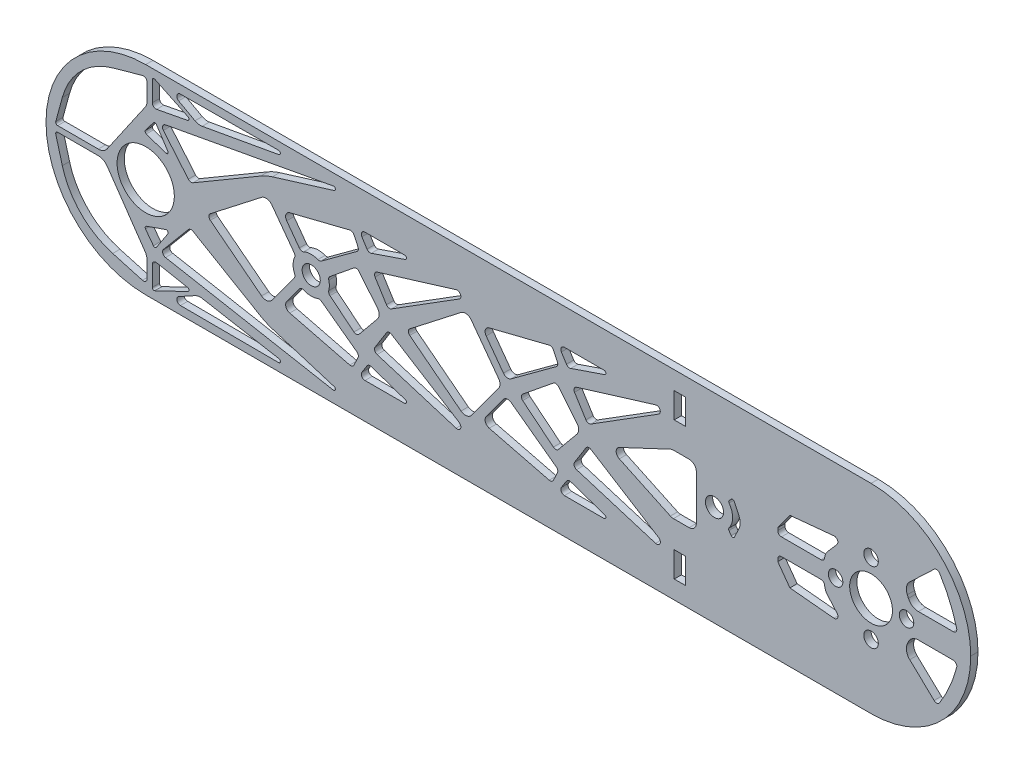
SolidWorks part; units mm, degrees
ref_plane "Front Plane" through (0, 0, 0) normal (0, 0, 1) x (1, 0, 0)
ref_plane "Top Plane" through (0, 0, 0) normal (0, 1, 0) x (1, 0, 0)
ref_plane "Right Plane" through (0, 0, 0) normal (1, 0, 0) x (0, 0, -1)
sketch "Sketch1" plane through (0, 0, 0) normal (0, 0, 1) x (1, 0, 0)
  line L1 (27.49, 0) -> (227.51, 0)
  line L2 (0, 27.49) -> (0, 27.51)
  line L3 (27.49, 55) -> (227.51, 55)
  line L4 (255, 27.49) -> (255, 27.51)
  arc A0 (227.51, 0) -> (255, 27.49) centre (227.51, 27.49) ccw
  arc A1 (227.51, 55) -> (255, 27.51) centre (227.51, 27.51) cw
  arc A2 (27.49, 0) -> (0, 27.49) centre (27.49, 27.49) cw
  arc A3 (27.49, 55) -> (0, 27.51) centre (27.49, 27.51) ccw
  point P9 (255, 55)
  point P12 (0, 0)
  point P15 (0, 55)
  dimension "D3" = 27.49
  dimension "D1" = 255
  dimension "D2" = 55
extrude "Boss-Extrude1" add sketch "Sketch1" along normal blind 2
sketch "Sketch2" plane through (0, 0, 2) normal (0, 0, 1) x (1, 0, 0)
  circle A0 centre (227.51, 27.51) radius 5.9
  circle A1 centre (27.49, 27.51) radius 7.9
  arc A2 (27.49, 55) -> (0, 27.51) centre (27.49, 27.51) ccw construction
  circle A3 centre (227.51, 27.51) radius 9.78
  circle A4 centre (217.73, 27.51) radius 2
  circle A5 centre (227.51, 37.29) radius 2
  circle A6 centre (237.29, 27.51) radius 2
  circle A7 centre (227.51, 17.73) radius 2
  point P17 (227.51, 27.51)
  dimension "D1" = 11.8
  dimension "D2" = 15.8
  dimension "D3" = 19.56
  dimension "D4" = 4
  dimension "D5" = 4
extrude "Cut-Extrude1" cut sketch "Sketch2" against normal through all contours A0 | A3 A5 | A3 A5 | A3 A4 | A3 A6 | A3 A6 | A3 A4 | A1 | A3 A7 | A3 A7
sketch "Sketch3" plane through (0, 0, 2) normal (0, 0, 1) x (1, 0, 0)
  line L5 (26.856, 20.2813) -> (28.4607, 20.2813)
  line L6 (26.856, 20.2813) -> (26.856, 19.5714)
  line L7 (26.856, 19.5714) -> (28.4607, 19.5714)
  line L8 (28.4607, 20.2813) -> (28.4607, 19.5714)
sketch "Sketch5" plane through (0, 0, 2) normal (0, 0, 1) x (1, 0, 0)
  line L0 (53.49, 5) -> (99.2465, 45)
  line L1 (53.49, 45) -> (99.2465, 45)
  line L2 (53.49, 45) -> (53.49, 5)
  line L3 (53.49, 5) -> (99.2465, 5)
  line L4 (99.2465, 45) -> (99.2465, 5)
  line L5 (53.49, 45) -> (99.2465, 5)
  line L6 (54.1482, 4.2471) -> (99.9046, 44.2471)
  line L7 (52.8318, 5.7529) -> (98.5883, 45.7529)
  line L8 (52.8318, 44.2471) -> (98.5883, 4.2471)
  line L9 (54.1482, 45.7529) -> (99.9046, 5.7529)
  line L10 (103.49, 5) -> (149.2465, 45)
  line L11 (103.49, 45) -> (149.2465, 45)
  line L12 (103.49, 45) -> (103.49, 5)
  line L13 (103.49, 5) -> (149.2465, 5)
  line L14 (149.2465, 45) -> (149.2465, 5)
  line L15 (103.49, 45) -> (149.2465, 5)
  line L16 (104.1482, 4.2471) -> (149.9046, 44.2471)
  line L17 (102.8318, 5.7529) -> (148.5883, 45.7529)
  line L18 (102.8318, 44.2471) -> (148.5883, 4.2471)
  line L19 (104.1482, 45.7529) -> (149.9046, 5.7529)
  line L20 (153.49, 5) -> (199.2465, 45)
  line L21 (153.49, 45) -> (199.2465, 45)
  line L22 (153.49, 45) -> (153.49, 5)
  line L23 (153.49, 5) -> (199.2465, 5)
  line L24 (199.2465, 45) -> (199.2465, 5)
  line L25 (153.49, 45) -> (199.2465, 5)
  line L26 (154.1482, 4.2471) -> (199.9046, 44.2471)
  line L27 (152.8318, 5.7529) -> (198.5883, 45.7529)
  line L28 (152.8318, 44.2471) -> (198.5883, 4.2471)
  line L29 (154.1482, 45.7529) -> (199.9046, 5.7529)
  line L30 (203.49, 5) -> (249.2465, 45)
  line L31 (203.49, 45) -> (249.2465, 45)
  line L32 (203.49, 45) -> (203.49, 5)
  line L33 (203.49, 5) -> (249.2465, 5)
  line L34 (249.2465, 45) -> (249.2465, 5)
  line L35 (203.49, 45) -> (249.2465, 5)
  line L36 (204.1482, 4.2471) -> (249.9046, 44.2471)
  line L37 (202.8318, 5.7529) -> (248.5883, 45.7529)
  line L38 (202.8318, 44.2471) -> (248.5883, 4.2471)
  line L39 (204.1482, 45.7529) -> (249.9046, 5.7529)
  line L40 (27.49, 0) -> (227.51, 0) construction
  line L41 (53.49, 25) -> (76.3682, 45)
  line L42 (76.3682, 45) -> (99.2465, 25)
  line L43 (99.2465, 25) -> (76.3682, 5)
  line L44 (76.3682, 5) -> (53.49, 25)
  line L45 (51.9706, 25) -> (76.3682, 46.3282)
  line L46 (76.3682, 46.3282) -> (100.7658, 25)
  line L47 (100.7658, 25) -> (76.3682, 3.6718)
  line L48 (76.3682, 3.6718) -> (51.9706, 25)
  line L49 (55.0094, 25) -> (76.3682, 43.6718)
  line L50 (76.3682, 43.6718) -> (97.7271, 25)
  line L51 (97.7271, 25) -> (76.3682, 6.3282)
  line L52 (76.3682, 6.3282) -> (55.0094, 25)
  line L53 (105.0094, 25) -> (126.3682, 43.6718)
  line L54 (101.9706, 25) -> (126.3682, 46.3282)
  line L55 (126.3682, 43.6718) -> (147.7271, 25)
  line L56 (126.3682, 46.3282) -> (150.7658, 25)
  line L57 (150.7658, 25) -> (126.3682, 3.6718)
  line L58 (147.7271, 25) -> (126.3682, 6.3282)
  line L59 (126.3682, 6.3282) -> (105.0094, 25)
  line L60 (126.3682, 3.6718) -> (101.9706, 25)
  line L61 (155.0094, 25) -> (176.3682, 43.6718)
  line L62 (151.9706, 25) -> (176.3682, 46.3282)
  line L63 (176.3682, 43.6718) -> (197.7271, 25)
  line L64 (176.3682, 46.3282) -> (200.7658, 25)
  line L65 (200.7658, 25) -> (176.3682, 3.6718)
  line L66 (197.7271, 25) -> (176.3682, 6.3282)
  line L67 (176.3682, 6.3282) -> (155.0094, 25)
  line L68 (176.3682, 3.6718) -> (151.9706, 25)
  line L69 (205.0094, 25) -> (226.3682, 43.6718)
  line L70 (201.9706, 25) -> (226.3682, 46.3282)
  line L71 (226.3682, 43.6718) -> (247.7271, 25)
  line L72 (226.3682, 46.3282) -> (250.7658, 25)
  line L73 (250.7658, 25) -> (226.3682, 3.6718)
  line L74 (247.7271, 25) -> (226.3682, 6.3282)
  line L75 (226.3682, 6.3282) -> (205.0094, 25)
  line L76 (226.3682, 3.6718) -> (201.9706, 25)
  dimension "D7" = 40
  dimension "D8" = 5
  dimension "D1" = 1
  dimension "D2" = 1
  dimension "D3" = 1
  dimension "D4" = 1
  dimension "D9" = 1
  dimension "D10" = 1
  dimension "D5" = 4
  dimension "D11" = 4
extrude "Cut-Extrude7" [suppressed] cut sketch "Sketch5" against normal blind 10 contours L75 L37 L38 L69 | L32 L70 L38 | L39 L70 L31 | L71 L69 L39 L37 | L31 L72 L37 | L36 L72 L34 | L74 L71 L36 L39 | L34 L73 L39 | L38 L73 L33 | L75 L74 L38 L36 | L33 L76 L36 | L37 L76 L32 | L24 L65 L29 | L28 L65 L23 | L67 L66 L28 L26 | L66 L63 L26 L29 | L26 L64 L24 | L21 L64 L27 | L63 L61 L29 L27 | L67 L27 L28 L61 | L27 L68 L22 | L23 L68 L26 | L22 L62 L28 | L29 L62 L21 | L18 L57 L13 | L14 L57 L19 | L58 L55 L16 L19 | L16 L56 L14 | L59 L58 L18 L16 | L13 L60 L16 | L17 L60 L12 | L59 L17 L18 L53 | L55 L53 L19 L17 | L11 L56 L17 | L19 L54 L11 | L12 L54 L18 | L4 L47 L9 | L8 L47 L3 | L52 L51 L8 L6 | L51 L50 L6 L9 | L6 L46 L4 | L1 L46 L7 | L50 L49 L9 L7 | L52 L7 L8 L49 | L2 L45 L8 | L7 L48 L2 | L3 L48 L6 | L9 L45 L1
sketch "Sketch7" plane through (0, 0, 2) normal (0, 0, 1) x (1, 0, 0)
  line L0 (0, 27.49) -> (255, 27.51) construction
  line L1 (59.4407, 39.2596) -> (45.3072, 28.2834)
  line L2 (46.3778, 27.4936) -> (70.6726, 27.4955)
  line L3 (69.7968, 26.3076) -> (62.2781, 16.1218)
  line L4 (69.7966, 28.6834) -> (62.2764, 38.868)
  line L5 (59.4426, 15.7298) -> (45.3073, 26.7037)
  line L6 (66.3676, 37.131) -> (71.1401, 30.6311)
  line L7 (73.2369, 30.3097) -> (85.7182, 39.4738)
  line L8 (86.0297, 40.7087) -> (84.9059, 43.0763)
  line L9 (83.7595, 43.6175) -> (67.2123, 39.4738)
  line L10 (87.1039, 43.6667) -> (88.5202, 41.4401)
  line L11 (89.6871, 41.0304) -> (99.0589, 44.2302)
  line L12 (98.8973, 45.2034) -> (87.9477, 45.2034)
  line L13 (90.7426, 35.8539) -> (93.8832, 30.8489)
  line L14 (95.2614, 30.5332) -> (113.9262, 42.2328)
  line L15 (113.1016, 44.0361) -> (91.2961, 37.3414)
  line L16 (158.0853, 28.8598) -> (183.7384, 40.9274)
  line L17 (185.729, 40.2195) -> (191.0035, 29.2363)
  line L18 (191.8349, 27.505) -> (155.1994, 27.5022)
  line L19 (185.731, 14.7897) -> (191.0038, 25.7737)
  line L20 (158.0855, 26.145) -> (183.7405, 14.0814)
  line L21 (76.448, 28.2722) -> (84.909, 35.1452)
  line L22 (86.3126, 35.0033) -> (91.43, 28.7656)
  line L23 (92.4706, 27.4973) -> (75.4923, 27.4959)
  line L24 (86.3138, 19.9903) -> (91.4302, 26.2288)
  line L25 (76.4481, 26.7198) -> (84.9102, 19.8481)
  line L26 (113.1042, 10.9617) -> (91.2977, 17.6529)
  line L27 (95.2619, 24.4618) -> (113.9285, 12.7651)
  line L28 (90.7439, 19.1403) -> (93.8838, 24.1458)
  line L29 (98.9001, 9.7921) -> (87.9505, 9.7904)
  line L30 (89.6892, 13.9636) -> (99.0615, 10.7653)
  line L31 (87.1065, 11.3269) -> (88.5224, 13.5538)
  line L32 (83.7621, 11.3756) -> (67.2142, 15.5167)
  line L33 (86.0318, 14.2848) -> (84.9083, 11.917)
  line L34 (73.2374, 24.6818) -> (85.72, 15.5196)
  line L35 (66.3691, 17.8594) -> (71.1406, 24.3601)
  line L36 (32.3699, 41.7077) -> (39.2566, 33.5015)
  line L37 (40.5286, 33.2818) -> (59.2382, 44.257)
  line L38 (62.4141, 45.6547) -> (79.4526, 50.9005)
  line L39 (79.2147, 51.8701) -> (32.9544, 43.334)
  line L40 (29.6243, 42.1853) -> (27.4391, 39.2765)
  line L41 (27.6724, 38.5047) -> (33.0193, 36.6169)
  line L42 (33.6032, 37.3636) -> (30.4415, 42.1602)
  line L43 (33.6048, 17.6217) -> (30.4438, 12.8246)
  line L44 (27.6741, 16.4797) -> (33.0207, 18.3683)
  line L45 (29.6266, 12.7993) -> (27.441, 15.7078)
  line L46 (79.2185, 3.1224) -> (32.9569, 11.6512)
  line L47 (62.4169, 9.3351) -> (79.4562, 4.092)
  line L48 (40.5295, 21.7046) -> (59.2408, 10.7323)
  line L49 (32.3721, 13.2774) -> (39.2575, 21.4847)
  line L50 (41.0795, 48.3745) -> (36.5711, 50.8626)
  line L51 (37.0652, 52.7381) -> (64.1368, 52.8435)
  line L52 (64.2272, 51.8514) -> (43.0596, 48.0483)
  line L53 (3.2327, 28.2834) -> (14.4162, 28.2834)
  line L54 (16.8868, 29.5817) -> (27.3295, 44.7433)
  line L55 (27.8588, 46.445) -> (27.8588, 50.9822)
  line L56 (2.6923, 28.9903) -> (4.4983, 35.6339)
  line L57 (18.3898, 49.6422) -> (26.5884, 51.945)
  line L58 (29.3043, 52.2893) -> (29.3043, 46.7923)
  line L59 (30.4915, 45.81) -> (39.0051, 47.4324)
  line L60 (39.1277, 48.3745) -> (30.0204, 52.7401)
  line L61 (39.1309, 6.6117) -> (30.0244, 2.2446)
  line L62 (30.4944, 9.1748) -> (39.0083, 7.5537)
  line L63 (29.3082, 2.6953) -> (29.3073, 8.1923)
  line L64 (18.3933, 5.3406) -> (26.5922, 3.0392)
  line L65 (2.6925, 25.9901) -> (4.4996, 19.3468)
  line L66 (27.8618, 8.5394) -> (27.8625, 4.0021)
  line L67 (16.8872, 25.4009) -> (27.3322, 10.241)
  line L68 (3.2328, 26.6971) -> (14.4163, 26.6989)
  line L69 (64.231, 3.1387) -> (43.0628, 6.9385)
  line L70 (37.0692, 2.2477) -> (64.1408, 2.1465)
  line L71 (41.0827, 6.612) -> (36.5748, 4.1231)
  line L72 (201.7924, 23.448) -> (205.1305, 18.8389)
  line L73 (114.4407, 39.2639) -> (100.3072, 28.2877)
  line L74 (201.7918, 31.5637) -> (201.7917, 30.8594)
  line L75 (202.7917, 29.8594) -> (213.707, 29.8594)
  line L76 (214.6964, 30.7146) -> (214.7547, 31.113)
  line L77 (215.4612, 32.6494) -> (218.1111, 35.691)
  line L78 (217.2611, 37.3433) -> (205.1291, 36.1732)
  line L79 (237.4989, 33.3977) -> (237.8131, 32.6921)
  line L80 (240.5537, 30.9122) -> (250.1576, 30.9122)
  line L81 (251.1234, 32.1712) -> (251.122, 32.1766)
  line L82 (246.347, 43.1132) -> (246.4336, 42.9755)
  line L83 (244.8991, 43.1688) -> (238.1756, 36.795)
  line L84 (244.9016, 11.8496) -> (238.1771, 18.2223)
  line L85 (246.3495, 11.9054) -> (246.4361, 12.0432)
  line L86 (251.1242, 22.8482) -> (251.1227, 22.8428)
  line L87 (240.5543, 24.1055) -> (250.1581, 24.107)
  line L88 (237.4998, 21.6195) -> (237.8139, 22.3252)
  line L89 (217.2627, 17.6708) -> (205.1305, 18.8389)
  line L90 (215.462, 22.3644) -> (218.1124, 19.3232)
  line L91 (214.6969, 24.2991) -> (214.7553, 23.9007)
  line L92 (202.7921, 25.1525) -> (213.7073, 25.1542)
  line L93 (201.7924, 23.448) -> (201.7923, 24.1522)
  line L94 (201.7918, 31.5637) -> (205.1291, 36.1732)
  line L95 (101.3778, 27.498) -> (125.6726, 27.4999)
  line L96 (124.7968, 26.3119) -> (117.2781, 16.1261)
  line L97 (124.7966, 28.6877) -> (117.2764, 38.8723)
  line L98 (114.4426, 15.7341) -> (100.3073, 26.708)
  line L99 (121.3676, 37.1353) -> (126.1401, 30.6354)
  line L100 (128.2369, 30.314) -> (140.7182, 39.4781)
  line L101 (141.0297, 40.713) -> (139.9059, 43.0806)
  line L102 (138.7595, 43.6219) -> (122.2123, 39.4781)
  line L103 (142.1039, 43.671) -> (143.5202, 41.4444)
  line L104 (144.6871, 41.0347) -> (154.0589, 44.2346)
  line L105 (153.8973, 45.2077) -> (142.9477, 45.2077)
  line L106 (145.7426, 35.8582) -> (148.8832, 30.8532)
  line L107 (150.2614, 30.5375) -> (168.9262, 42.2371)
  line L108 (168.1016, 44.0404) -> (146.2961, 37.3457)
  line L109 (131.448, 28.2765) -> (139.909, 35.1495)
  line L110 (141.3126, 35.0076) -> (146.43, 28.7699)
  line L111 (147.4706, 27.5016) -> (130.4923, 27.5002)
  line L112 (141.3138, 19.9946) -> (146.4302, 26.2331)
  line L113 (131.4481, 26.7241) -> (139.9102, 19.8525)
  line L114 (168.1042, 10.966) -> (146.2977, 17.6572)
  line L115 (150.2619, 24.4661) -> (168.9285, 12.7694)
  line L116 (145.7439, 19.1446) -> (148.8838, 24.1501)
  line L117 (153.9001, 9.7964) -> (142.9505, 9.7947)
  line L118 (144.6892, 13.968) -> (154.0615, 10.7696)
  line L119 (142.1065, 11.3312) -> (143.5224, 13.5581)
  line L120 (138.7621, 11.3799) -> (122.2142, 15.521)
  line L121 (141.0318, 14.2891) -> (139.9083, 11.9213)
  line L122 (128.2374, 24.6861) -> (140.72, 15.5239)
  line L123 (121.3691, 17.8637) -> (126.1406, 24.3644)
  line L124 (55, 27.4943) -> (310, 27.5143) construction
  line L125 (172.5741, 35.6756) -> (187.9112, 35.6756)
  line L126 (172.5754, 19.3315) -> (187.9124, 19.3339)
  arc A0 (62.2764, 38.868) -> (59.4407, 39.2596) centre (60.6674, 37.68) ccw
  arc A1 (45.3073, 26.7037) -> (45.3072, 28.2834) centre (45.9206, 27.4936) cw
  arc A2 (69.7968, 26.3076) -> (69.7966, 28.6834) centre (68.1877, 27.4953) ccw
  arc A3 (62.2781, 16.1218) -> (59.4426, 15.7298) centre (60.669, 17.3095) cw
  arc A4 (113.9262, 42.2328) -> (113.1016, 44.0361) centre (113.3951, 43.0801) ccw
  arc A5 (90.7426, 35.8539) -> (91.2961, 37.3414) centre (91.5896, 36.3855) cw
  arc A6 (93.8832, 30.8489) -> (95.2614, 30.5332) centre (94.7303, 31.3805) ccw
  arc A7 (87.1039, 43.6667) -> (87.9477, 45.2034) centre (87.9477, 44.2034) cw
  arc A8 (88.5202, 41.4401) -> (89.6871, 41.0304) centre (89.364, 41.9768) ccw
  arc A9 (99.0589, 44.2302) -> (98.8973, 45.2034) centre (98.8973, 44.7034) ccw
  arc A10 (85.7182, 39.4738) -> (86.0297, 40.7087) centre (85.1263, 40.2799) ccw
  arc A11 (84.9059, 43.0763) -> (83.7595, 43.6175) centre (84.0025, 42.6475) ccw
  arc A12 (66.3676, 37.131) -> (67.2123, 39.4738) centre (67.5767, 38.0187) cw
  arc A13 (71.1401, 30.6311) -> (73.2369, 30.3097) centre (72.3492, 31.5188) ccw
  arc A14 (158.0855, 26.145) -> (158.0853, 28.8598) centre (158.7238, 27.5024) cw
  arc A15 (185.731, 14.7897) -> (183.7405, 14.0814) centre (184.3788, 15.4388) cw
  arc A16 (183.7384, 40.9274) -> (185.729, 40.2195) centre (184.3769, 39.5701) cw
  arc A17 (191.0035, 29.2363) -> (191.0038, 25.7737) centre (187.3977, 27.5047) cw
  arc A18 (76.4481, 26.7198) -> (76.448, 28.2722) centre (77.0785, 27.496) cw
  arc A19 (86.3138, 19.9903) -> (84.9102, 19.8481) centre (85.5406, 20.6244) cw
  arc A20 (84.909, 35.1452) -> (86.3126, 35.0033) centre (85.5395, 34.369) cw
  arc A21 (91.4302, 26.2288) -> (91.43, 28.7656) centre (89.8838, 27.497) ccw
  arc A22 (71.1406, 24.3601) -> (73.2374, 24.6818) centre (72.3498, 23.4725) cw
  arc A23 (66.3691, 17.8594) -> (67.2142, 15.5167) centre (67.5784, 16.9719) ccw
  arc A24 (84.9083, 11.917) -> (83.7621, 11.3756) centre (84.0048, 12.3457) cw
  arc A25 (85.72, 15.5196) -> (86.0318, 14.2848) centre (85.1283, 14.7135) cw
  arc A26 (99.0615, 10.7653) -> (98.9001, 9.7921) centre (98.9, 10.2921) cw
  arc A27 (88.5224, 13.5538) -> (89.6892, 13.9636) centre (89.3662, 13.0172) cw
  arc A28 (87.1065, 11.3269) -> (87.9505, 9.7904) centre (87.9503, 10.7904) ccw
  arc A29 (93.8838, 24.1458) -> (95.2619, 24.4618) centre (94.7309, 23.6144) cw
  arc A30 (90.7439, 19.1403) -> (91.2977, 17.6529) centre (91.591, 18.6089) ccw
  arc A31 (113.9285, 12.7651) -> (113.1042, 10.9617) centre (113.3975, 11.9177) cw
  arc A32 (39.2566, 33.5015) -> (40.5286, 33.2818) centre (40.0226, 34.1443) ccw
  arc A33 (32.3699, 41.7077) -> (32.9544, 43.334) centre (33.1359, 42.3506) cw
  arc A34 (59.2382, 44.257) -> (62.4141, 45.6547) centre (66.8278, 31.3188) cw
  arc A35 (79.4526, 50.9005) -> (79.2147, 51.8701) centre (79.3054, 51.3784) ccw
  arc A36 (33.0193, 36.6169) -> (33.6032, 37.3636) centre (33.1858, 37.0884) ccw
  arc A37 (27.4391, 39.2765) -> (27.6724, 38.5047) centre (27.8389, 38.9762) ccw
  arc A38 (29.6243, 42.1853) -> (30.4415, 42.1602) centre (30.0241, 41.885) cw
  arc A39 (29.6266, 12.7993) -> (30.4438, 12.8246) centre (30.0263, 13.0997) ccw
  arc A40 (27.441, 15.7078) -> (27.6741, 16.4797) centre (27.8407, 16.0082) cw
  arc A41 (33.0207, 18.3683) -> (33.6048, 17.6217) centre (33.1873, 17.8968) cw
  arc A42 (79.4562, 4.092) -> (79.2185, 3.1224) centre (79.3092, 3.6141) cw
  arc A43 (59.2408, 10.7323) -> (62.4169, 9.3351) centre (66.8284, 23.6717) ccw
  arc A44 (32.3721, 13.2774) -> (32.9569, 11.6512) centre (33.1382, 12.6346) ccw
  arc A45 (39.2575, 21.4847) -> (40.5295, 21.7046) centre (40.0236, 20.842) cw
  arc A46 (117.2764, 38.8723) -> (114.4407, 39.2639) centre (115.6674, 37.6843) ccw
  arc A47 (36.5711, 50.8626) -> (37.0652, 52.7381) centre (37.0543, 51.7382) cw
  arc A48 (64.2272, 51.8514) -> (64.1368, 52.8435) centre (64.1387, 52.3435) ccw
  arc A49 (41.0795, 48.3745) -> (43.0596, 48.0483) centre (42.5291, 51.001) ccw
  arc A50 (27.3295, 44.7433) -> (27.8588, 46.445) centre (24.8588, 46.445) ccw
  arc A51 (14.4162, 28.2834) -> (16.8868, 29.5817) centre (14.4162, 31.2834) ccw
  arc A52 (27.8588, 50.9822) -> (26.5884, 51.945) centre (26.8588, 50.9822) ccw
  arc A53 (3.2327, 28.2834) -> (2.6923, 28.9903) centre (3.2327, 28.8434) cw
  arc A54 (4.4983, 35.6339) -> (18.3898, 49.6422) centre (23.7979, 30.3873) cw
  arc A55 (29.3043, 46.7923) -> (30.4915, 45.81) centre (30.3043, 46.7923) ccw
  arc A56 (39.0051, 47.4324) -> (39.1277, 48.3745) centre (38.9115, 47.9236) ccw
  arc A57 (29.3043, 52.2893) -> (30.0204, 52.7401) centre (29.8043, 52.2893) cw
  arc A58 (29.3082, 2.6953) -> (30.0244, 2.2446) centre (29.8082, 2.6954) ccw
  arc A59 (39.0083, 7.5537) -> (39.1309, 6.6117) centre (38.9147, 7.0625) cw
  arc A60 (29.3073, 8.1923) -> (30.4944, 9.1748) centre (30.3073, 8.1925) cw
  arc A61 (4.4996, 19.3468) -> (18.3933, 5.3406) centre (23.7984, 24.5964) ccw
  arc A62 (3.2328, 26.6971) -> (2.6925, 25.9901) centre (3.2329, 26.1371) ccw
  arc A63 (27.8625, 4.0021) -> (26.5922, 3.0392) centre (26.8625, 4.002) cw
  arc A64 (14.4163, 26.6989) -> (16.8872, 25.4009) centre (14.4168, 23.6989) cw
  arc A65 (27.3322, 10.241) -> (27.8618, 8.5394) centre (24.8618, 8.5389) cw
  arc A66 (41.0827, 6.612) -> (43.0628, 6.9385) centre (42.5327, 3.9857) cw
  arc A67 (64.231, 3.1387) -> (64.1408, 2.1465) centre (64.1426, 2.6465) cw
  arc A68 (36.5748, 4.1231) -> (37.0692, 2.2477) centre (37.0581, 3.2477) ccw
  arc A69 (100.3073, 26.708) -> (100.3072, 28.2877) centre (100.9206, 27.4979) cw
  arc A70 (124.7968, 26.3119) -> (124.7966, 28.6877) centre (123.1877, 27.4997) ccw
  arc A71 (213.707, 29.8594) -> (214.6964, 30.7146) centre (213.707, 30.8594) ccw
  arc A72 (201.7917, 30.8594) -> (202.7917, 29.8594) centre (202.7917, 30.8594) ccw
  arc A73 (214.7547, 31.113) -> (215.4612, 32.6494) centre (217.7231, 30.6787) cw
  arc A74 (218.1111, 35.691) -> (217.2611, 37.3433) centre (217.3571, 36.3479) ccw
  arc A75 (237.8131, 32.6921) -> (240.5537, 30.9122) centre (240.5537, 33.9122) ccw
  arc A76 (237.4989, 33.3977) -> (238.1756, 36.795) centre (240.2396, 34.6179) cw
  arc A77 (251.122, 32.1766) -> (246.347, 43.1132) centre (212.4863, 21.8187) ccw
  arc A78 (250.1576, 30.9122) -> (251.1234, 32.1712) centre (250.1576, 31.9122) ccw
  arc A79 (246.4336, 42.9755) -> (244.8991, 43.1688) centre (245.5871, 42.4431) ccw
  arc A80 (246.4361, 12.0432) -> (244.9016, 11.8496) centre (245.5894, 12.5754) cw
  arc A81 (250.1581, 24.107) -> (251.1242, 22.8482) centre (250.1582, 23.107) cw
  arc A82 (251.1227, 22.8428) -> (246.3495, 11.9054) centre (212.4854, 33.1946) cw
  arc A83 (237.4998, 21.6195) -> (238.1771, 18.2223) centre (240.2407, 20.3998) ccw
  arc A84 (237.8139, 22.3252) -> (240.5543, 24.1055) centre (240.5547, 21.1055) cw
  arc A85 (218.1124, 19.3232) -> (217.2627, 17.6708) centre (217.3585, 18.6662) cw
  arc A86 (214.7553, 23.9007) -> (215.462, 22.3644) centre (217.7236, 24.3354) ccw
  arc A87 (201.7923, 24.1522) -> (202.7921, 25.1525) centre (202.7923, 24.1525) cw
  arc A88 (213.7073, 25.1542) -> (214.6969, 24.2991) centre (213.7075, 24.1542) cw
  arc A89 (117.2781, 16.1261) -> (114.4426, 15.7341) centre (115.669, 17.3139) cw
  arc A90 (168.9262, 42.2371) -> (168.1016, 44.0404) centre (168.3951, 43.0844) ccw
  arc A91 (145.7426, 35.8582) -> (146.2961, 37.3457) centre (146.5896, 36.3898) cw
  arc A92 (148.8832, 30.8532) -> (150.2614, 30.5375) centre (149.7303, 31.3848) ccw
  arc A93 (142.1039, 43.671) -> (142.9477, 45.2077) centre (142.9477, 44.2077) cw
  arc A94 (143.5202, 41.4444) -> (144.6871, 41.0347) centre (144.364, 41.9811) ccw
  arc A95 (154.0589, 44.2346) -> (153.8973, 45.2077) centre (153.8973, 44.7077) ccw
  arc A96 (140.7182, 39.4781) -> (141.0297, 40.713) centre (140.1263, 40.2842) ccw
  arc A97 (139.9059, 43.0806) -> (138.7595, 43.6219) centre (139.0025, 42.6518) ccw
  arc A98 (121.3676, 37.1353) -> (122.2123, 39.4781) centre (122.5767, 38.0231) cw
  arc A99 (126.1401, 30.6354) -> (128.2369, 30.314) centre (127.3492, 31.5231) ccw
  arc A100 (131.4481, 26.7241) -> (131.448, 28.2765) centre (132.0785, 27.5004) cw
  arc A101 (141.3138, 19.9946) -> (139.9102, 19.8525) centre (140.5406, 20.6287) cw
  arc A102 (139.909, 35.1495) -> (141.3126, 35.0076) centre (140.5395, 34.3733) cw
  arc A103 (146.4302, 26.2331) -> (146.43, 28.7699) centre (144.8838, 27.5014) ccw
  arc A104 (126.1406, 24.3644) -> (128.2374, 24.6861) centre (127.3498, 23.4769) cw
  arc A105 (121.3691, 17.8637) -> (122.2142, 15.521) centre (122.5784, 16.9762) ccw
  arc A106 (139.9083, 11.9213) -> (138.7621, 11.3799) centre (139.0048, 12.35) cw
  arc A107 (140.72, 15.5239) -> (141.0318, 14.2891) centre (140.1283, 14.7178) cw
  arc A108 (154.0615, 10.7696) -> (153.9001, 9.7964) centre (153.9, 10.2964) cw
  arc A109 (143.5224, 13.5581) -> (144.6892, 13.968) centre (144.3662, 13.0216) cw
  arc A110 (142.1065, 11.3312) -> (142.9505, 9.7947) centre (142.9503, 10.7947) ccw
  arc A111 (148.8838, 24.1501) -> (150.2619, 24.4661) centre (149.7309, 23.6187) cw
  arc A112 (145.7439, 19.1446) -> (146.2977, 17.6572) centre (146.591, 18.6132) ccw
  arc A113 (168.9285, 12.7694) -> (168.1042, 10.966) centre (168.3975, 11.922) cw
  point P10 (61.0591, 40.5164)
  point P58 (185.0871, 13.4482)
  point P61 (185.0849, 41.5608)
  point P74 (85.6827, 19.2208)
  point P77 (85.6814, 35.7726)
  point P161 (32.2541, 52.0519)
  point P167 (42.0116, 47.86)
  point P178 (27.2336, 52.5087)
  point P181 (2.5001, 28.2834)
  point P184 (7.473, 46.576)
  point P229 (7.476, 8.4051)
  point P230 (2.5002, 26.697)
  point P231 (27.2376, 2.4756)
  point P232 (42.0148, 7.1266)
  point P233 (32.258, 2.9332)
  point P245 (216.3912, 27.507)
  point P248 (209.2458, 27.5064)
  dimension "D1" = 2
  dimension "D2" = 1
  dimension "D3" = 2
  dimension "D4" = 1
  dimension "D5" = 1
  dimension "D6" = 1
  dimension "D7" = 1
  dimension "D8" = 0.5
  dimension "D9" = 1
  dimension "D10" = 1.5
  dimension "D11" = 1.5
  dimension "D12" = 1.5
  dimension "D13" = 4
  dimension "D14" = 1
  dimension "D15" = 1
  dimension "D16" = 2
  dimension "D17" = 1
  dimension "D18" = 15
  dimension "D19" = 0.5
  dimension "D20" = 0.5
  dimension "D21" = 2
  dimension "D22" = 1
  dimension "D23" = 0.5
  dimension "D24" = 3
  dimension "D25" = 3
  dimension "D26" = 1
  dimension "D27" = 20
  dimension "D28" = 1
  dimension "D29" = 0.5
  dimension "D30" = 1
  dimension "D31" = 3
  dimension "D32" = 1
  dimension "D33" = 3
  dimension "D34" = 40
  dimension "D35" = 1
extrude "Cut-Extrude9" cut sketch "Sketch7" against normal blind 10
extrude "Cut-Extrude10" [suppressed] cut sketch "Sketch3" against normal through all
sketch "Sketch8" plane through (0, 0, 2) normal (0, 0, 1) x (1, 0, 0)
  line L0 (173.2349, 27.51) -> (176.3349, 27.51) construction
  line L1 (173.2349, 50.01) -> (176.3349, 50.01)
  line L2 (173.2349, 50.01) -> (173.2349, 5.01)
  line L3 (173.2349, 5.01) -> (176.3349, 5.01)
  line L4 (176.3349, 50.01) -> (176.3349, 5.01)
  line L5 (233.41, 27.51) -> (221.61, 27.51) construction
  line L7 (173.2349, 50.01) -> (176.3349, 50.01)
  line L8 (173.2349, 50.01) -> (173.2349, 43.01)
  line L9 (173.2349, 43.01) -> (176.3349, 43.01)
  line L10 (176.3349, 50.01) -> (176.3349, 43.01)
  line L11 (173.2349, 5.01) -> (176.3349, 5.01)
  line L12 (173.2349, 5.01) -> (173.2349, 12.01)
  line L13 (173.2349, 12.01) -> (176.3349, 12.01)
  line L14 (176.3349, 5.01) -> (176.3349, 12.01)
  circle A0 centre (227.51, 27.51) radius 5.9 construction
  dimension "D1" = 3.1
  dimension "D2" = 45
  dimension "D3" = 7
  dimension "D4" = 7
extrude "Cut-Extrude11" cut sketch "Sketch8" against normal through all contours L2 L9 L4 L1 | L13 L2 L3 L4
sketch "Sketch9" plane through (0, 0, 2) normal (0, 0, 1) x (1, 0, 0)
  line L0 (176.3349, 50.01) -> (176.3349, 43.01) construction
  line L1 (179.3349, 27.7378) -> (179.3349, 35.6756)
  line L2 (172.5741, 35.6756) -> (187.9112, 35.6756) construction
  line L3 (179.3349, 35.6756) -> (179.3349, 19.3326)
  line L4 (172.5754, 19.3315) -> (187.9124, 19.3339) construction
  line L5 (188.096, 31.0324) -> (189.4573, 32.4559)
  line L6 (187.9112, 35.6756) -> (191.0035, 29.2363) construction
  line L7 (188.096, 24.4433) -> (189.4581, 22.5538)
  line L8 (187.9124, 19.3339) -> (191.0038, 25.7737) construction
  line L9 (189.4573, 32.4559) -> (189.4581, 22.5538) construction
  line L10 (172.5741, 35.6756) -> (187.9112, 35.6756)
  line L11 (187.9112, 35.6756) -> (191.0035, 29.2363)
  line L12 (187.9124, 19.3339) -> (191.0038, 25.7737)
  line L13 (172.5754, 19.3315) -> (187.9124, 19.3339)
  circle A0 centre (184.3349, 27.7378) radius 2.5
  circle A1 centre (184.3349, 27.7378) radius 5
  dimension "D1" = 5
  dimension "D2" = 10
  dimension "D3" = 8
extrude "Boss-Extrude2" add sketch "Sketch9" against normal blind 2 contours A1 L5 L11 L10 L1 | A1 A0 | A1 L3 L13 L12 L7
fillet "Fillet1" radius 2 4 edges at (172.5754, 19.3315, 1) (172.5741, 35.6756, 1) (179.3349, 19.3326, 1) (179.3349, 35.6756, 1)
fillet "Fillet2" radius 0.5 4 edges at (189.4581, 22.5538, 1) (188.096, 24.4433, 1) (188.096, 31.0324, 1) (189.4573, 32.4559, 1)
sketch "Sketch10" plane through (0, 0, 2) normal (0, 0, 1) x (1, 0, 0)
  line L0 (68.1331, 27.51) -> (78.1331, 27.51) construction
  line L1 (35.39, 27.51) -> (19.59, 27.51) construction
  line L2 (70.1877, 27.4955) -> (76.0785, 27.496) construction
  circle A0 centre (73.1331, 27.51) radius 5
  circle A1 centre (73.1331, 27.51) radius 2.5
  circle A2 centre (27.49, 27.51) radius 7.9 construction
  arc A3 (69.7968, 26.3076) -> (69.7966, 28.6834) centre (68.1877, 27.4953) ccw construction
  arc A4 (76.448, 28.2722) -> (76.4481, 26.7198) centre (77.0785, 27.496) ccw construction
  point P18 (73.1331, 27.4957)
  dimension "D1" = 10
  dimension "D2" = 5
extrude "Boss-Extrude3" add sketch "Sketch10" against normal blind 2
sketch "Sketch11" plane through (0, 0, 2) normal (0, 0, 1) x (1, 0, 0)
  circle A0 centre (73.1331, 27.51) radius 2.5
  arc A1 (75.4549, 31.9382) -> (70.3713, 31.6781) centre (73.1331, 27.51) ccw construction
  dimension "D1" = 5
extrude "Cut-Extrude12" cut sketch "Sketch11" against normal through all
fillet "Fillet3" radius 1 8 edges at (70.3861, 23.3322, 1) (75.4329, 23.0703, 1) (68.8188, 24.9827, 1) (68.8091, 30.0207, 1) (70.3713, 31.6781, 1) (75.4549, 31.9382, 1) (77.7721, 25.6446, 1) (77.7804, 29.3546, 1)
sketch "Sketch12" plane through (0, 0, 2) normal (0, 0, 1) x (1, 0, 0)
  circle A0 centre (27.49, 27.51) radius 5.2448
  circle A1 centre (227.51, 27.51) radius 3.4806
